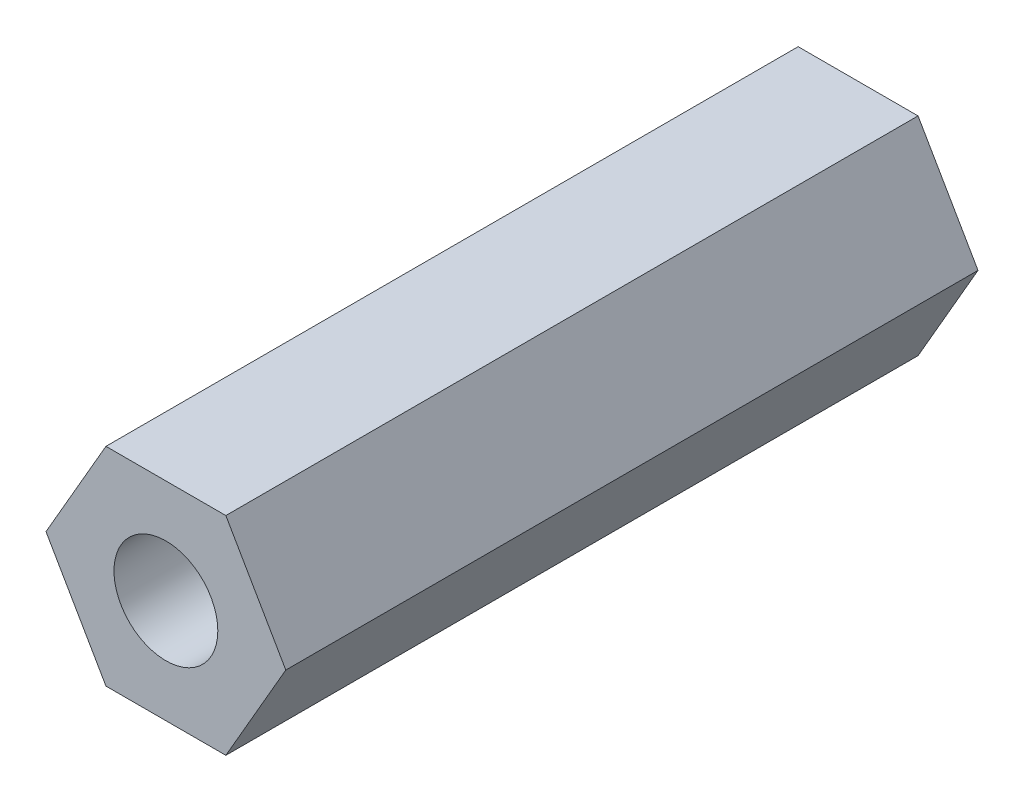
SolidWorks part; units mm, degrees
material "1060 Alloy"
ref_plane "Front Plane" through (0, 0, 0) normal (0, 0, 1) x (1, 0, 0)
ref_plane "Top Plane" through (0, 0, 0) normal (0, 1, 0) x (1, 0, 0)
ref_plane "Right Plane" through (0, 0, 0) normal (1, 0, 0) x (0, 0, -1)
sketch "Sketch1" plane through (0, 0, 0) normal (0, 0, 1) x (1, 0, 0)
  line L1 (3.4641, 0) -> (1.7321, 3)
  line L2 (1.7321, 3) -> (-1.7321, 3)
  line L3 (-1.7321, 3) -> (-3.4641, 0)
  line L4 (-3.4641, 0) -> (-1.7321, -3)
  line L5 (-1.7321, -3) -> (1.7321, -3)
  line L6 (1.7321, -3) -> (3.4641, 0)
  circle A0 centre (0, 0) radius 2.5
  circle A1 centre (0, 0) radius 1.5
  circle A2 centre (0, 0) radius 3 construction
extrude "Boss-Extrude1" add sketch "Sketch1" along normal blind 20 contours A0 A1 | L5 L6 L1 L2 L3 L4 A0
